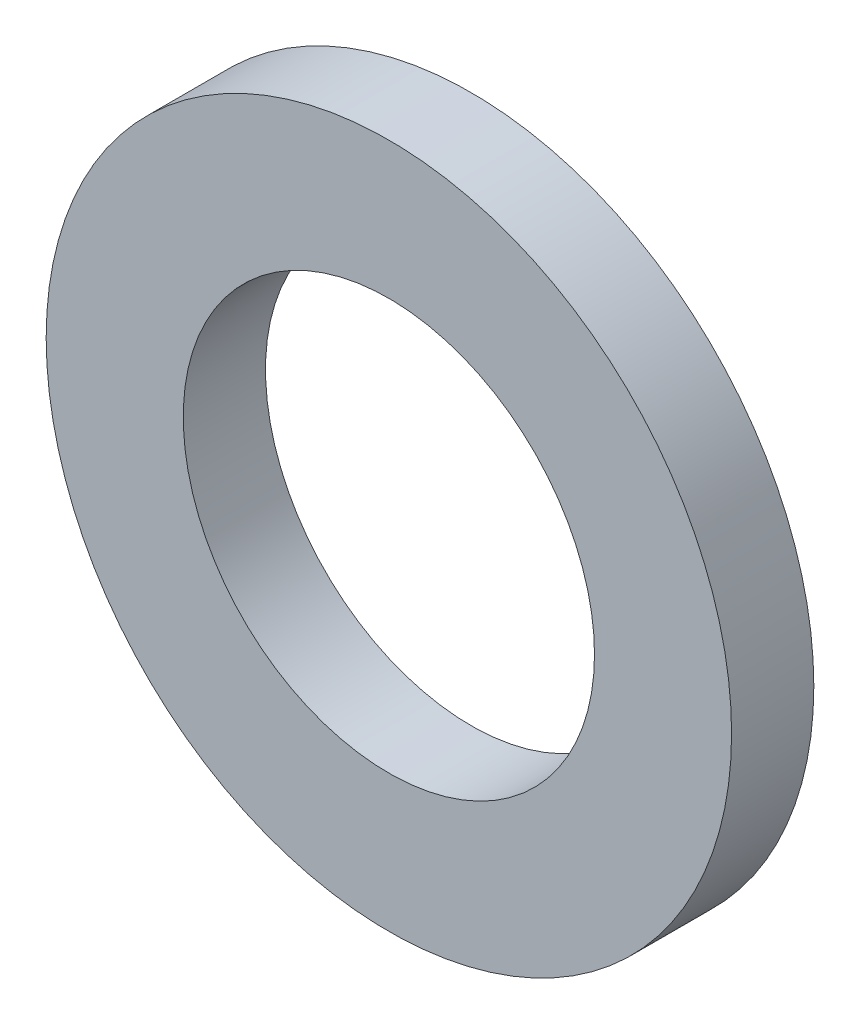
SolidWorks part; units mm, degrees
material "아크릴(내충격성)"
ref_plane "정면" through (0, 0, 0) normal (0, 0, 1) x (1, 0, 0)
ref_plane "윗면" through (0, 0, 0) normal (0, 1, 0) x (1, 0, 0)
ref_plane "우측면" through (0, 0, 0) normal (1, 0, 0) x (0, 0, -1)
sketch "스케치1" plane through (0, 0, 0) normal (0, 0, 1) x (1, 0, 0)
  circle A0 centre (0, 0) radius 7.5
  circle A1 centre (0, 0) radius 12.5
  dimension "D1" = 25
  dimension "D2" = 15
extrude "보스-돌출1" add sketch "스케치1" along normal blind 3
